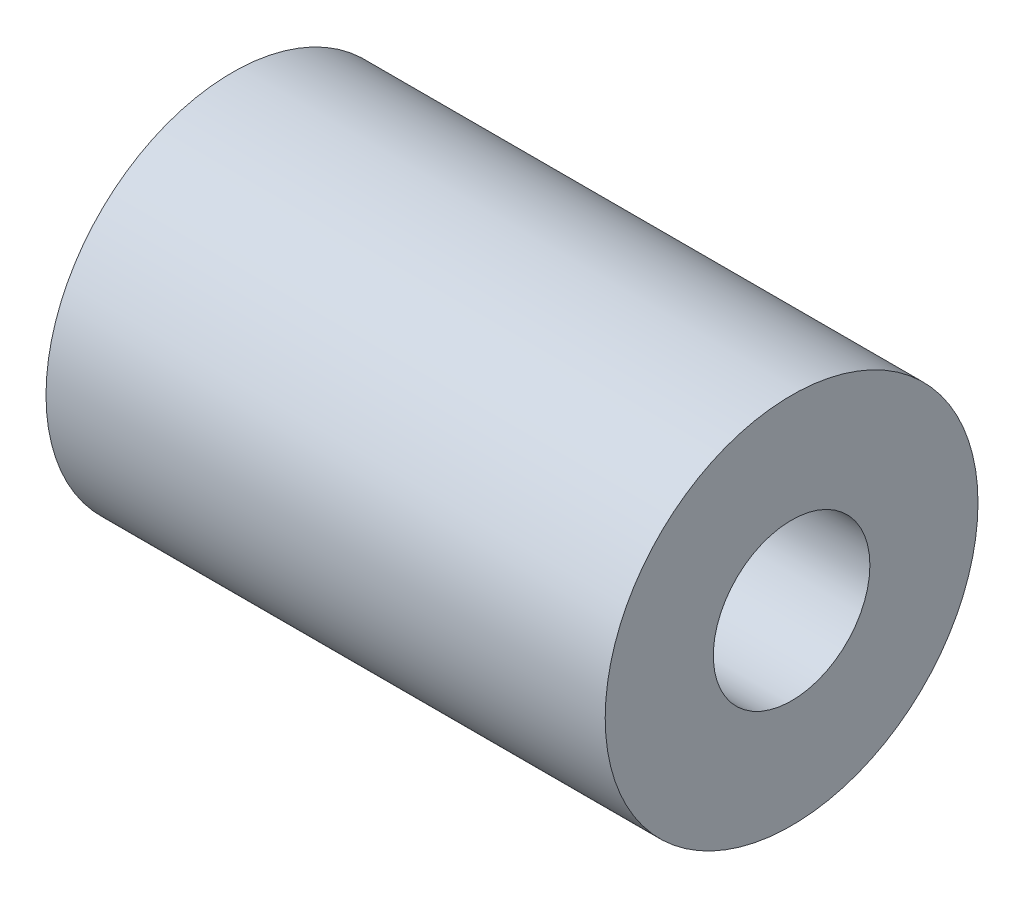
SolidWorks part; units mm, degrees
material "2.0367 (CuZn40)"
ref_plane "Vorne" through (0, 0, 0) normal (0, 0, 1) x (1, 0, 0)
ref_plane "Oben" through (0, 0, 0) normal (0, 1, 0) x (1, 0, 0)
ref_plane "Rechts" through (0, 0, 0) normal (1, 0, 0) x (0, 0, -1)
sketch "Skizze1" plane through (0, 0, 0) normal (0, 0, 1) x (1, 0, 0)
  line L0 (5.5, 0) -> (-5.5, 0) construction
  line L1 (7.5, 0) -> (-7.5, 0)
  line L3 (7.5, 5) -> (-7.5, 5)
  line L4 (-7.5, 0) -> (-7.5, 5)
  line L5 (0, -5.5) -> (0, 5.5) construction
  line L6 (0, 0) -> (15.0629, 0) construction
  line L7 (7.5, 5) -> (7.5, 0)
  point P6 (0, 5)
  dimension "D1" = 10
  dimension "D2" = 15
revolve "Rotation1" add sketch "Skizze1" angle 360 about L6
hole_wizard "M5 Gewindebohrung1" positions "Skizze2" profile "Skizze3" tap size "M5" standard "DIN" end condition through all
sketch "Skizze2" plane through (7.5, 0, 0) normal (1, 0, 0) x (0, 0, -1)
  point P0 (0, 0)
sketch "Skizze3" plane through (7.5, 0, 0) normal (0, 1, 0) x (0, 0, -1)
  line L0 (0, 0) -> (0, 15)
  line L1 (0, 15) -> (2.1, 15)
  line L2 (2.1, 15) -> (2.1, 0)
  line L5 (2.1, 0) -> (0, 0)
  line L11 (0, -6.35) -> (0, 107.95) construction
  dimension "Bohrerdurchmesser" = 4.2
  dimension "Bohrungstiefe" = 15
cosmetic thread "Bohrungsgewinde1"
